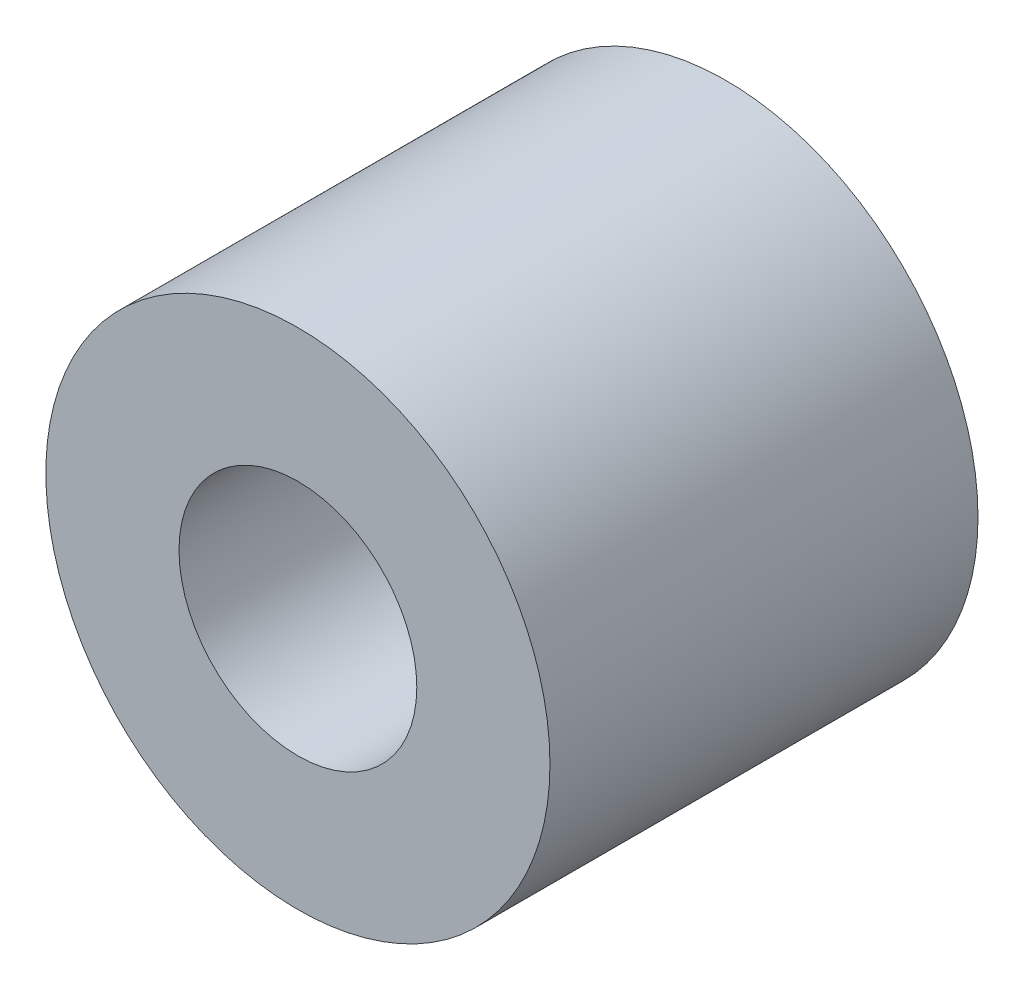
SolidWorks part; units mm, degrees
ref_plane "Спереди" through (0, 0, 0) normal (0, 0, 1) x (1, 0, 0)
ref_plane "Сверху" through (0, 0, 0) normal (0, 1, 0) x (1, 0, 0)
ref_plane "Справа" through (0, 0, 0) normal (1, 0, 0) x (0, 0, -1)
sketch "Эскиз1" plane through (0, 0, 0) normal (0, 0, 1) x (1, 0, 0)
  circle A0 centre (0, 0) radius 265
  circle A1 centre (0, 0) radius 125
  dimension "D1" = 530
  dimension "D2" = 250
extrude "Бобышка-Вытянуть1" add sketch "Эскиз1" along normal blind 450
